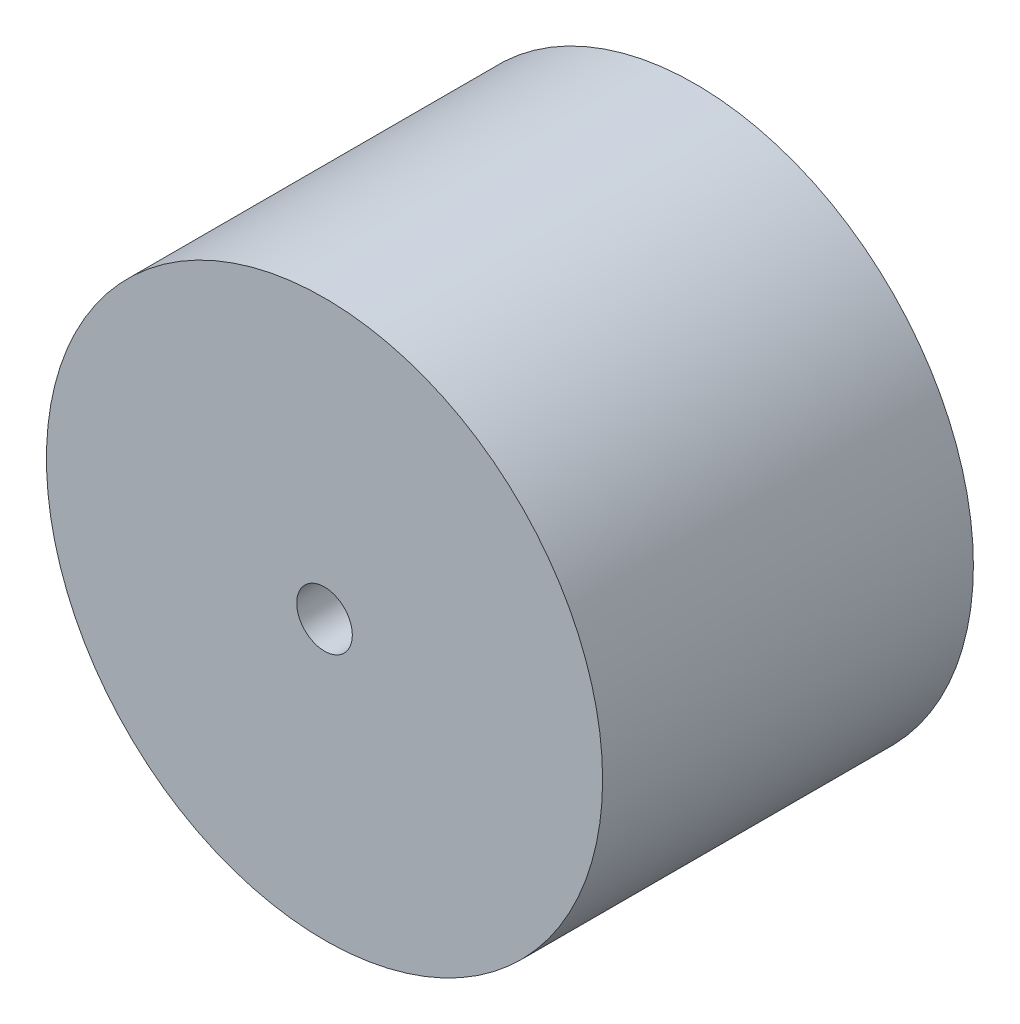
SolidWorks part; units mm, degrees
ref_plane "Alzado" through (0, 0, 0) normal (0, 0, 1) x (1, 0, 0)
ref_plane "Planta" through (0, 0, 0) normal (0, 1, 0) x (1, 0, 0)
ref_plane "Vista lateral" through (0, 0, 0) normal (1, 0, 0) x (0, 0, -1)
sketch "Croquis1" plane through (0, 0, 0) normal (0, 0, 1) x (1, 0, 0)
  circle A0 centre (0, 0) radius 15
  dimension "D1" = 30
extrude "Saliente-Extruir1" add sketch "Croquis1" along normal blind 20
sketch "Croquis2" plane through (0, 0, 0) normal (0, 0, -1) x (-1, 0, 0)
  circle A0 centre (0, 0) radius 8
  dimension "D1" = 16
extrude "Cortar-Extruir1" cut sketch "Croquis2" against normal blind 13
sketch "Croquis3" plane through (0, 0, 20) normal (0, 0, 1) x (1, 0, 0)
  circle A0 centre (0, 0) radius 1.5
  dimension "D1" = 3
extrude "Cortar-Extruir2" cut sketch "Croquis3" against normal up to next
